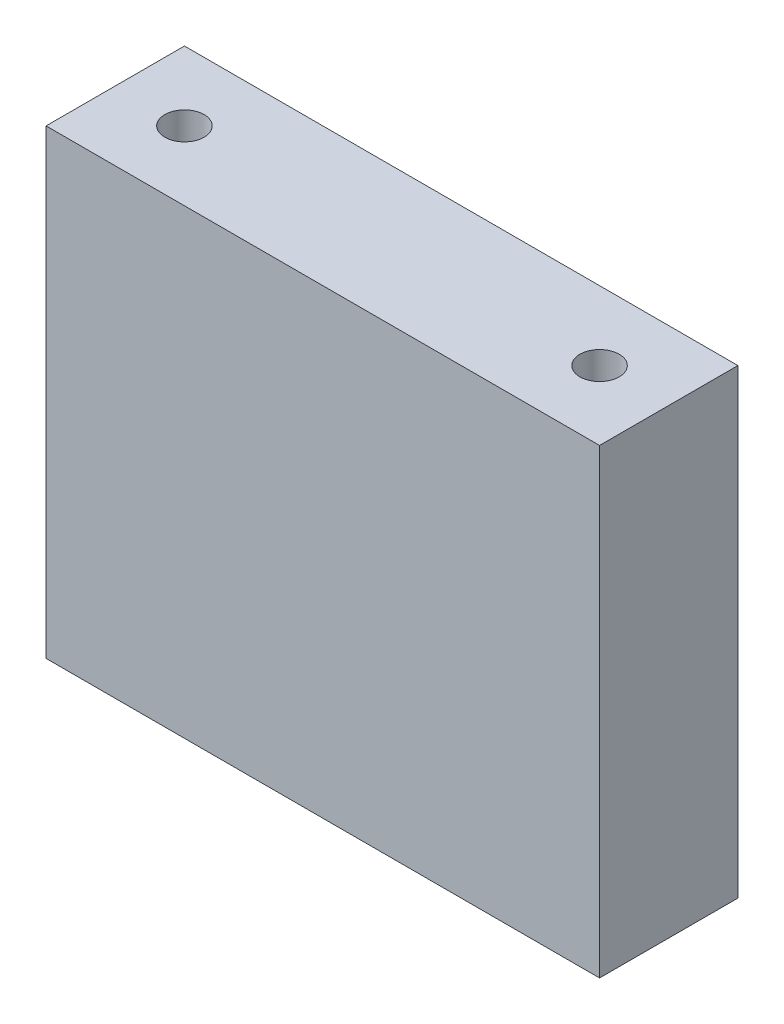
SolidWorks part; units mm, degrees
ref_plane "Front Plane" through (0, 0, 0) normal (0, 0, 1) x (1, 0, 0)
ref_plane "Top Plane" through (0, 0, 0) normal (0, 1, 0) x (1, 0, 0)
ref_plane "Right Plane" through (0, 0, 0) normal (1, 0, 0) x (0, 0, -1)
sketch "Sketch1" plane through (0, 0, 0) normal (0, 0, 1) x (1, 0, 0)
  line L1 (-19.05, 15.875) -> (19.05, 15.875)
  line L2 (-19.05, 15.875) -> (-19.05, -15.875)
  line L3 (-19.05, -15.875) -> (19.05, -15.875)
  line L4 (19.05, 15.875) -> (19.05, -15.875)
  line L5 (-19.05, 15.875) -> (19.05, -15.875) construction
  line L6 (-19.05, -15.875) -> (19.05, 15.875) construction
  point P0 (0, 0)
  dimension "D1" = 31.75
  dimension "D2" = 38.1
extrude "Boss-Extrude1" add sketch "Sketch1" along normal blind 9.525
sketch "Sketch2" plane through (0, 15.875, 0) normal (0, 1, 0) x (1, 0, 0)
  line L0 (-19.05, -9.525) -> (-19.05, 0) construction
  line L1 (19.05, -9.525) -> (19.05, 0) construction
  circle A0 centre (-14.2875, -4.7625) radius 2.54
  circle A1 centre (14.2875, -4.7625) radius 2.54
  point P9 (-19.05, -4.7625)
  dimension "D1" = 5.08
  dimension "D2" = 4.7625
  dimension "D3" = 4.7625
hole_wizard "#6-32 Tapped Hole1" positions "Sketch3" profile "Sketch4" tap size "#6-32" standard "ANSI Inch"
sketch "Sketch3" plane through (0, 15.875, 0) normal (0, 1, 0) x (1, 0, 0)
  point P0 (-14.2875, -4.7625)
  point P3 (14.2875, -4.7625)
sketch "Sketch4" plane through (-14.2875, 15.875, 4.7625) normal (1, 0, 0) x (0, 0, 1)
  line L0 (0, 0) -> (0, 8.4327)
  line L1 (0, 8.4327) -> (1.3525, 7.62)
  line L2 (1.3525, 7.62) -> (1.3525, 0)
  line L5 (1.3525, 0) -> (0, 0)
  line L10 (0, 8.4327) -> (-1.3526, 7.62) construction
  line L11 (0, -6.35) -> (0, 107.95) construction
  dimension "Tap Drill Dia." = 2.7051
  dimension "Tap Drill Depth" = 7.62
  dimension "Drill Angle" = 118
cosmetic thread "Hole Thread1" parameters "D1"=7.0104, "D2"=3.5052
cosmetic thread "Hole Thread2" parameters "D1"=7.0104, "D2"=3.5052
hole_wizard "#6-32 Tapped Hole2" positions "Sketch5" profile "Sketch6" tap size "#6-32" standard "ANSI Inch"
sketch "Sketch5" plane through (0, -15.875, 0) normal (0, -1, 0) x (-1, 0, 0)
  point P0 (-14.2875, -4.7625)
  point P3 (14.2875, -4.7625)
sketch "Sketch6" plane through (14.2875, -15.875, 4.7625) normal (1, 0, 0) x (0, 0, -1)
  line L0 (0, 0) -> (0, 10.2005)
  line L1 (0, 10.2005) -> (1.3525, 9.3878)
  line L2 (1.3525, 9.3878) -> (1.3525, 0)
  line L5 (1.3525, 0) -> (0, 0)
  line L10 (0, 10.2005) -> (-1.3526, 9.3878) construction
  line L11 (0, -6.35) -> (0, 107.95) construction
  dimension "Tap Drill Dia." = 2.7051
  dimension "Tap Drill Depth" = 9.3878
  dimension "Drill Angle" = 118
cosmetic thread "Hole Thread3" parameters "D1"=7.0104, "D2"=3.5052
cosmetic thread "Hole Thread4" parameters "D1"=7.0104, "D2"=3.5052
